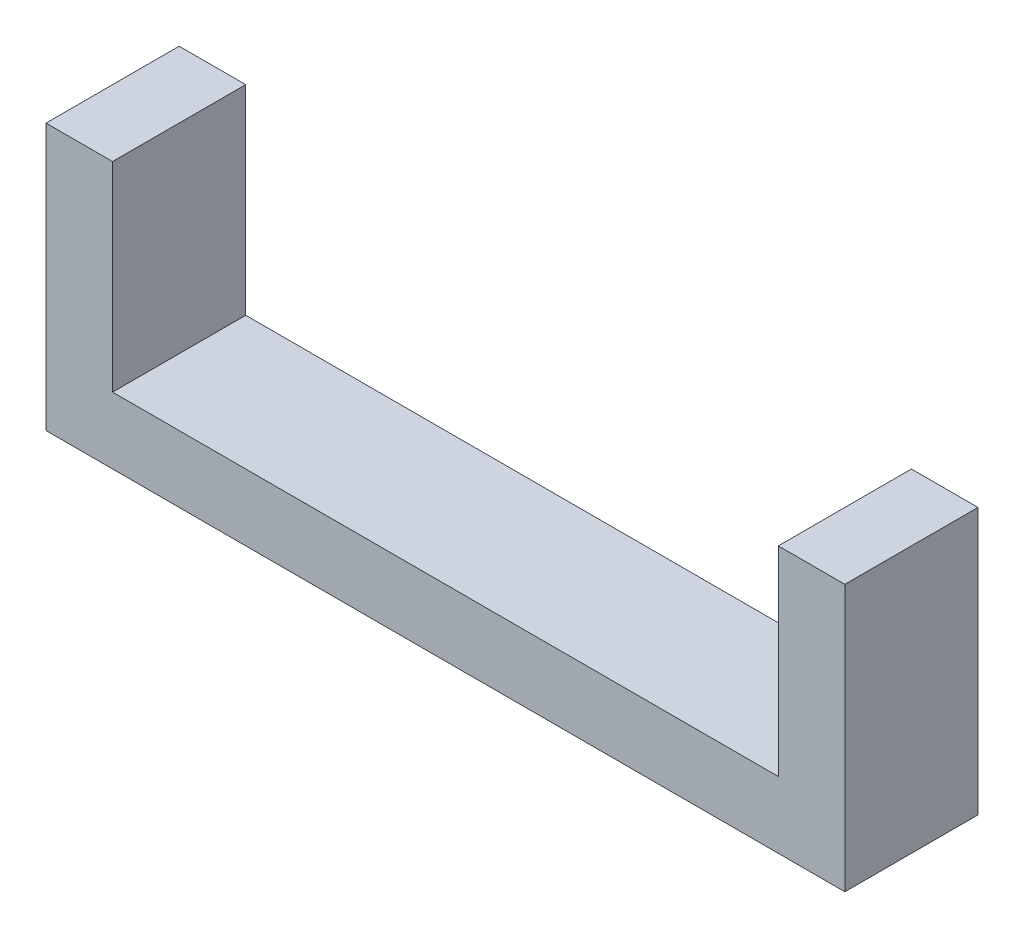
SolidWorks part; units mm, degrees
ref_plane "Front Plane" through (0, 0, 0) normal (0, 0, 1) x (1, 0, 0)
ref_plane "Top Plane" through (0, 0, 0) normal (0, 1, 0) x (1, 0, 0)
ref_plane "Right Plane" through (0, 0, 0) normal (1, 0, 0) x (0, 0, -1)
sketch "Sketch1" plane through (0, 0, 0) normal (0, 0, 1) x (1, 0, 0)
  line L0 (-38.1, 0) -> (38.1, 0)
  line L1 (38.1, 0) -> (38.1, 25.4)
  line L2 (38.1, 25.4) -> (31.75, 25.4)
  line L3 (31.75, 25.4) -> (31.75, 6.35)
  line L4 (31.75, 6.35) -> (-31.75, 6.35)
  line L5 (-31.75, 6.35) -> (-31.75, 25.4)
  line L6 (-31.75, 25.4) -> (-38.1, 25.4)
  line L7 (-38.1, 25.4) -> (-38.1, 0)
  point P9 (0, 0)
  dimension "D1" = 6.35
  dimension "D2" = 25.4
  dimension "D3" = 6.35
  dimension "D4" = 76.2
extrude "Boss-Extrude1" add sketch "Sketch1" along normal blind 12.7
